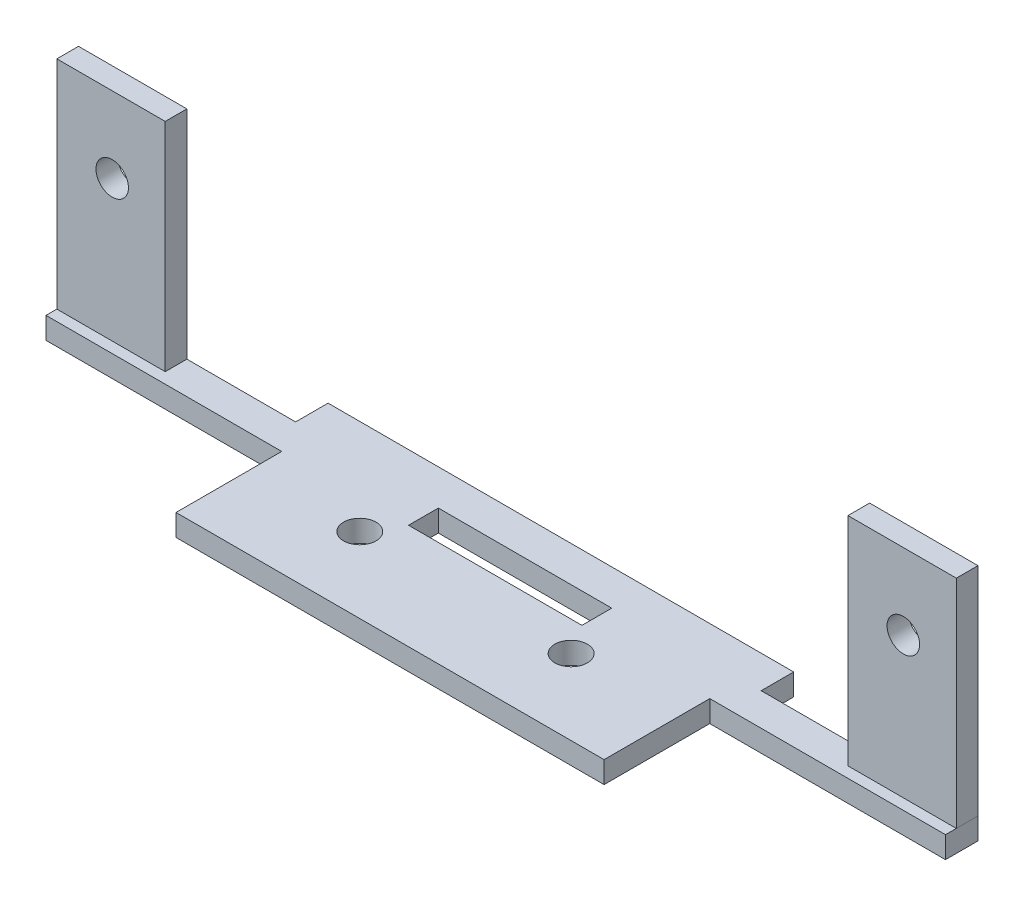
SolidWorks part; units mm, degrees
ref_plane "Front Plane" through (0, 0, 0) normal (0, 0, 1) x (1, 0, 0)
ref_plane "Top Plane" through (0, 0, 0) normal (0, 1, 0) x (1, 0, 0)
ref_plane "Right Plane" through (0, 0, 0) normal (1, 0, 0) x (0, 0, -1)
sketch "Sketch2" plane through (0, 0, 0) normal (0, 0, 1) x (1, 0, 0)
  line L0 (2.8346, 0) -> (2.8346, 20)
  line L1 (2.8346, 20) -> (12.8346, 20)
  line L2 (12.8346, 20) -> (12.8346, 0)
  line L3 (12.8346, 0) -> (2.8346, 0)
  line L5 (75.8346, 20) -> (85.8346, 20)
  line L6 (75.8346, 20) -> (75.8346, 0)
  line L7 (75.8346, 0) -> (85.8346, 0)
  line L8 (85.8346, 20) -> (85.8346, 0)
  point P8 (7.8346, 20)
  point P9 (80.8346, 20)
  dimension "D1" = 20
  dimension "D2" = 10
  dimension "D3" = 10
  dimension "D4" = 73
extrude "Boss-Extrude1" add sketch "Sketch2" along normal blind 2
sketch "Sketch6" plane through (0, 0, 0) normal (0, 0, -1) x (-1, 0, 0)
  line L0 (-75.8346, 0) -> (-85.8346, 0) construction
  line L1 (-2.8346, 0) -> (-12.8346, 0) construction
  circle A0 centre (-80.9435, 13) radius 1.5
  circle A1 centre (-7.9435, 13) radius 1.5
  dimension "D1" = 73
  dimension "D2" = 13
  dimension "D3" = 13
extrude "Cut-Extrude1" cut sketch "Sketch6" against normal blind 2
sketch "Sketch7" plane through (0, 0, 2) normal (0, 0, 1) x (1, 0, 0)
  line L1 (2.8346, 0) -> (85.8334, 0)
  line L2 (2.8346, 0) -> (2.8346, -2)
  line L3 (2.8346, -2) -> (85.8334, -2)
  line L4 (85.8334, 0) -> (85.8334, -2)
  dimension "D1" = 2
extrude "Boss-Extrude2" add sketch "Sketch7" along normal blind 15 and the other way blind 5 contours L2 L1 L4 L3
sketch "Sketch8" plane through (0, -2, 0) normal (0, -1, 0) x (1, 0, 0)
  line L0 (2.8346, -3) -> (2.8346, 17) construction
  line L1 (52.3346, 0.2963) -> (36.3346, 0.2963)
  line L2 (52.3346, 0.2963) -> (52.3346, 3.0463)
  line L3 (52.3346, 3.0463) -> (36.3346, 3.0463)
  line L4 (36.3346, 0.2963) -> (36.3346, 3.0463)
  line L5 (24.5846, 12.7527) -> (24.5846, 3)
  line L6 (24.5846, 3) -> (2.8346, 3)
  line L7 (85.8334, 3) -> (64.0846, 3)
  line L8 (85.8334, -3) -> (85.8334, 17) construction
  line L9 (64.0846, 3) -> (64.0846, 12.7527)
  line L10 (64.0846, 12.7527) -> (24.5846, 12.7527)
  line L11 (2.8346, 3) -> (2.8346, 17)
  line L12 (2.8346, 17) -> (85.8334, 17)
  line L13 (85.8334, 17) -> (85.8334, 3)
  line L14 (2.8346, -3) -> (85.8334, -3) construction
  circle A0 centre (54.0846, 5.7963) radius 1.5
  circle A1 centre (34.5846, 5.7963) radius 1.5
  dimension "D4" = 1.75
  dimension "D1" = 16
  dimension "D2" = 2.75
  dimension "D3" = 33.5
  dimension "D5" = 1.75
  dimension "D6" = 5.5
  dimension "D7" = 5.5
  dimension "D8" = 6
  dimension "D9" = 6
  dimension "D10" = 10
  dimension "D11" = 10
extrude "Cut-Extrude2" cut sketch "Sketch8" against normal blind 15
sketch "Sketch9" plane through (0, 0, 0) normal (0, 1, 0) x (1, 0, 0)
  line L9 (2.8346, 3) -> (22.865, 3)
  line L10 (2.8346, 3) -> (2.8346, 0)
  line L11 (2.8346, 0) -> (22.865, 0)
  line L12 (22.865, 3) -> (22.865, 0)
  line L13 (85.8334, 3) -> (65.8262, 3)
  line L14 (85.8334, 3) -> (85.8334, 0)
  line L15 (85.8334, 0) -> (65.8262, 0)
  line L16 (65.8262, 3) -> (65.8262, 0)
extrude "Cut-Extrude3" cut sketch "Sketch9" against normal blind 15
